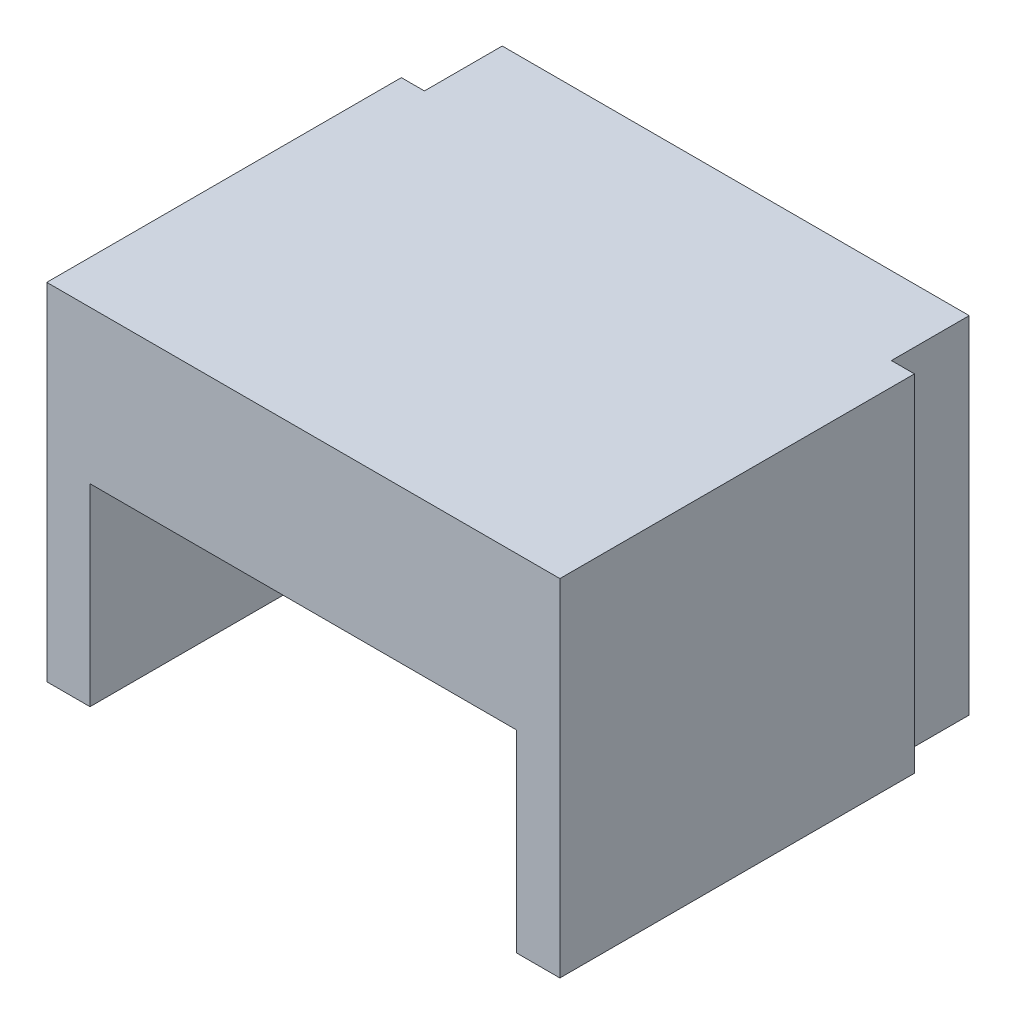
SolidWorks part; units mm, degrees
ref_plane "Front Plane" through (0, 0, 0) normal (0, 0, 1) x (1, 0, 0)
ref_plane "Top Plane" through (0, 0, 0) normal (0, 1, 0) x (1, 0, 0)
ref_plane "Right Plane" through (0, 0, 0) normal (1, 0, 0) x (0, 0, -1)
sketch "Sketch1" plane through (0, 0, 0) normal (0, 0, 1) x (1, 0, 0)
  line L1 (0, 0) -> (17.8, 0)
  line L2 (0, 0) -> (0, 12)
  line L3 (0, 12) -> (17.8, 12)
  line L4 (17.8, 0) -> (17.8, 12)
  dimension "D1" = 12
  dimension "D2" = 17.8
extrude "Boss-Extrude1" add sketch "Sketch1" along normal blind 15
sketch "Sketch2" plane through (0, 0, 15) normal (0, 0, 1) x (1, 0, 0)
  line L0 (8.25, 0) -> (-8.25, 0) construction
  line L1 (1.5, 0) -> (16.3, 0)
  line L2 (1.5, 0) -> (1.5, 7.5)
  line L3 (1.5, 7.5) -> (16.3, 7.5)
  line L4 (16.3, 0) -> (16.3, 7.5)
  line L5 (0, -6.6) -> (0, 6.6) construction
  line L6 (17.8, 0) -> (17.8, 12) construction
  dimension "D1" = 14.8
  dimension "D2" = 7.5
  dimension "D3" = 1.5
  dimension "D4" = 1.5
extrude "Cut-Extrude1" cut sketch "Sketch2" against normal through all
sketch "Sketch3" plane through (0, 7.5, 0) normal (0, -1, 0) x (1, 0, 0)
  line L0 (16.3, 0) -> (16.3, 15) construction
  line L1 (1.5, 15) -> (16.3, 15)
  line L2 (1.5, 15) -> (1.5, 3.55)
  line L3 (1.5, 3.55) -> (16.3, 3.55)
  line L4 (16.3, 15) -> (16.3, 3.55)
extrude "Boss-Extrude2" add sketch "Sketch3" along normal blind 0.8
sketch "Sketch4" plane through (0, 0, 0) normal (0, 0, -1) x (-1, 0, 0)
  line L0 (8.25, 0) -> (-8.25, 0) construction
  line L2 (-17, 0) -> (-17, 12)
  line L4 (-0.8, 0) -> (-0.8, 12)
  line L5 (-17.8, 12) -> (0, 12) construction
  line L6 (-17.8, 0) -> (-17.8, 12) construction
  line L7 (0, 6.6) -> (0, -6.6) construction
  line L9 (-17.8, 12) -> (-17, 12)
  line L10 (-17.8, 12) -> (-17.8, 0)
  line L11 (-17.8, 0) -> (-17, 0)
  line L13 (0, 12) -> (-0.8, 12)
  line L14 (0, 12) -> (0, 0)
  line L15 (0, 0) -> (-0.8, 0)
  dimension "D1" = 16.2
  dimension "D2" = 0.8
  dimension "D3" = 0.8
extrude "Cut-Extrude2" cut sketch "Sketch4" against normal blind 2.7
